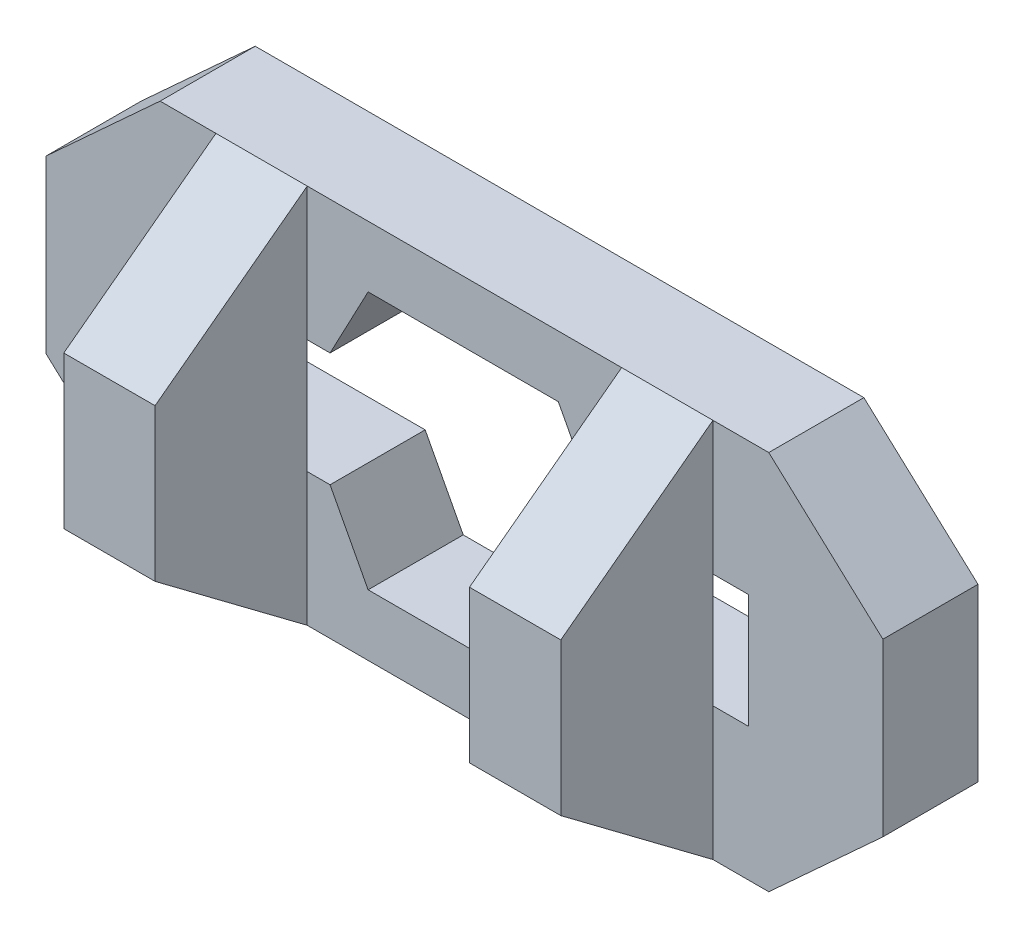
SolidWorks part; units mm, degrees
ref_plane "Front Plane" through (0, 0, 0) normal (0, 0, 1) x (1, 0, 0)
ref_plane "Top Plane" through (0, 0, 0) normal (0, 1, 0) x (1, 0, 0)
ref_plane "Right Plane" through (0, 0, 0) normal (1, 0, 0) x (0, 0, -1)
other "Configuration Table"
sketch "Sketch1" plane through (0, 0, 0) normal (0, 0, 1) x (1, 0, 0)
  line L0 (110, 22.5) -> (110, -22.5)
  line L1 (-80, 50) -> (80, 50)
  line L2 (-80, 50) -> (-110, 22.5)
  line L3 (-80, -50) -> (80, -50)
  line L4 (80, 50) -> (110, 22.5)
  line L5 (110, -22.5) -> (80, -50)
  line L6 (-110, 22.5) -> (-110, -22.5)
  line L7 (-110, -22.5) -> (-80, -50)
  line L8 (-75.3251, 15) -> (-35.3251, 15)
  line L9 (-35.3251, 15) -> (-25.3251, 33.9142)
  line L10 (-75.3251, 15) -> (-75.3251, -15)
  line L11 (-25.3251, 33.9142) -> (24.6749, 33.9142)
  line L12 (74.6749, 15) -> (74.6749, -15)
  line L13 (24.6749, 33.9142) -> (34.6749, 15)
  line L14 (34.6749, 15) -> (74.6749, 15)
  line L15 (-75.3251, -15) -> (-35.3251, -15)
  line L16 (-35.3251, -15) -> (-25.3251, -33.9142)
  line L17 (-25.3251, -33.9142) -> (24.6749, -33.9142)
  line L18 (24.6749, -33.9142) -> (34.6749, -15)
  line L19 (34.6749, -15) -> (74.6749, -15)
  point P4 (0, 50)
  point P9 (110, 0)
  point P11 (-110, 0)
  point P17 (74.6749, 0)
  dimension "D1" = 150
  dimension "D2" = 100
  dimension "D3" = 45
  dimension "D4" = 40
  dimension "D5" = 50
  dimension "D6" = 50
  dimension "D7" = 30
extrude "Extrude1" add sketch "Sketch1" along normal blind 25
ref_plane "Plane1" through (0, 0, 65) normal (0, 0, 1) x (1, 0, 0)
sketch "Sketch2" plane through (0, 0, 65) normal (0, 0, 1) x (1, 0, 0)
  line L0 (-75.3251, 15) -> (-75.3251, -15) construction
  line L1 (-65.3251, 20) -> (-41.3251, 20)
  line L2 (-65.3251, 20) -> (-65.3251, -20)
  line L3 (-65.3251, -20) -> (-41.3251, -20)
  line L4 (-41.3251, 20) -> (-41.3251, -20)
  line L5 (80, 50) -> (-80, 50) construction
  dimension "D1" = 24
  dimension "D2" = 40
  dimension "D3" = 10
  dimension "D4" = 30
sketch "Sketch3" plane through (0, 0, 25) normal (0, 0, 1) x (1, 0, 0)
  line L0 (-80, -50) -> (80, -50) construction
  line L1 (-65.3251, -50) -> (-41.3251, -50)
  line L2 (-65.3251, -50) -> (-65.3251, 50)
  line L3 (-65.3251, 50) -> (-41.3251, 50)
  line L4 (-41.3251, -50) -> (-41.3251, 50)
  line L5 (80, 50) -> (-80, 50) construction
  line L6 (-65.3251, 20) -> (-65.3251, -20) construction
  line L7 (-41.3251, 20) -> (-41.3251, -20) construction
loft "Loft1" add profiles "Sketch3", "Sketch2"
mirror "Mirror1" about plane through (0, 0, 0) normal (1, 0, 0) of "Loft1"
